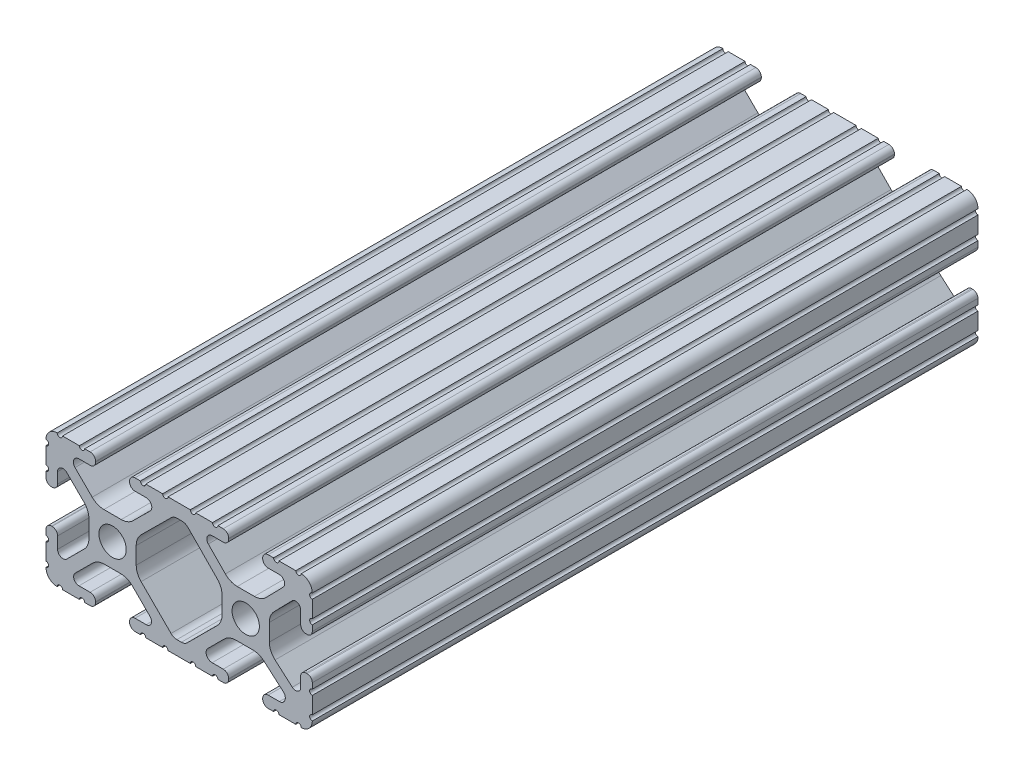
SolidWorks part; units mm, degrees
ref_plane "Front Plane" through (0, 0, 0) normal (0, 0, 1) x (1, 0, 0)
ref_plane "Top Plane" through (0, 0, 0) normal (0, 1, 0) x (1, 0, 0)
ref_plane "Right Plane" through (0, 0, 0) normal (1, 0, 0) x (0, 0, -1)
sketch "Sketch1" plane through (0, 0, 0) normal (0, 0, 1) x (1, 0, 0)
  line L0 (-7.2595, -3.8694) -> (-1.5457, -9.5728)
  line L1 (-8.1915, 1.6223) -> (-8.1915, -1.6223)
  line L2 (-1.504, 9.5765) -> (-7.252, 3.8768)
  line L3 (0.5515, 10.033) -> (-0.3952, 10.033)
  line L4 (7.2829, 3.8459) -> (1.6756, 9.5611)
  line L5 (8.1915, -1.6223) -> (8.1915, 1.6223)
  line L6 (1.5457, -9.5728) -> (7.2595, -3.8694)
  line L7 (-0.4332, -10.033) -> (0.4332, -10.033)
  line L8 (18.0171, 12.7) -> (16.9875, 12.7)
  line L9 (15.9385, 11.651) -> (15.9385, 11.5392)
  line L10 (16.9875, 10.4902) -> (19.1164, 10.4902)
  line L11 (19.8441, 8.7652) -> (16.619, 5.4551)
  line L12 (14.3449, 4.4958) -> (11.0833, 4.4958)
  line L13 (8.817, 5.4472) -> (5.5642, 8.7627)
  line L14 (6.2894, 10.4902) -> (8.4125, 10.4902)
  line L15 (9.4615, 11.5392) -> (9.4615, 11.651)
  line L16 (8.4125, 12.7) -> (7.3829, 12.7)
  line L17 (6.3669, 12.7) -> (3.1496, 12.7)
  line L18 (2.1336, 12.7) -> (-2.1336, 12.7)
  line L19 (-3.1496, 12.7) -> (-6.3669, 12.7)
  line L20 (-7.3829, 12.7) -> (-8.4125, 12.7)
  line L21 (-9.4615, 11.651) -> (-9.4615, 11.5392)
  line L22 (-8.4125, 10.4902) -> (-6.2836, 10.4902)
  line L23 (-5.5326, 8.6661) -> (-8.81, 5.4163)
  line L24 (-11.0455, 4.4958) -> (-14.3545, 4.4958)
  line L25 (-16.59, 5.4163) -> (-19.8674, 8.6661)
  line L26 (-19.1164, 10.4902) -> (-16.9875, 10.4902)
  line L27 (-15.9385, 11.5392) -> (-15.9385, 11.651)
  line L28 (-16.9875, 12.7) -> (-18.0171, 12.7)
  line L29 (-19.0331, 12.7) -> (-22.2504, 12.7)
  line L30 (-25.4, 9.5504) -> (-25.4, 6.3331)
  line L31 (-25.4, 5.3171) -> (-25.4, 4.2375)
  line L32 (-24.401, 3.2385) -> (-24.2392, 3.2385)
  line L33 (-23.1902, 4.2875) -> (-23.1902, 6.3347)
  line L34 (-21.434, 7.0665) -> (-18.148, 3.8082)
  line L35 (-17.2085, 1.5536) -> (-17.2085, -1.6952)
  line L36 (-18.1405, -3.9423) -> (-21.4316, -7.2274)
  line L37 (-23.1902, -6.498) -> (-23.1902, -4.2875)
  line L38 (-24.2392, -3.2385) -> (-24.351, -3.2385)
  line L39 (-25.4, -4.2875) -> (-25.4, -5.3171)
  line L40 (-25.4, -6.3331) -> (-25.4, -9.5504)
  line L41 (-22.2504, -12.7) -> (-19.0331, -12.7)
  line L42 (-18.0171, -12.7) -> (-16.9875, -12.7)
  line L43 (-15.9384, -11.651) -> (-15.9384, -11.5392)
  line L44 (-16.9875, -10.4902) -> (-19.1164, -10.4902)
  line L45 (-19.8341, -8.7551) -> (-16.4966, -5.4237)
  line L46 (-14.2536, -4.4958) -> (-11.1464, -4.4958)
  line L47 (-8.9034, -5.4237) -> (-5.5659, -8.7551)
  line L48 (-6.2836, -10.4902) -> (-8.4125, -10.4902)
  line L49 (-9.4616, -11.5392) -> (-9.4616, -11.651)
  line L50 (-8.4125, -12.7) -> (-7.3829, -12.7)
  line L51 (-6.3669, -12.7) -> (-3.1496, -12.7)
  line L52 (-2.1336, -12.7) -> (2.1336, -12.7)
  line L53 (3.1496, -12.7) -> (6.3669, -12.7)
  line L54 (7.3829, -12.7) -> (8.4125, -12.7)
  line L55 (9.4616, -11.651) -> (9.4616, -11.5392)
  line L56 (8.4125, -10.4902) -> (6.2894, -10.4902)
  line L57 (5.4807, -8.5353) -> (8.5979, -5.4237)
  line L58 (10.8409, -4.4958) -> (14.1026, -4.4958)
  line L59 (16.1879, -5.2766) -> (19.8682, -8.4822)
  line L60 (19.1164, -10.4902) -> (16.9875, -10.4902)
  line L61 (15.9384, -11.5392) -> (15.9384, -11.651)
  line L62 (16.9875, -12.7) -> (18.0171, -12.7)
  line L63 (19.0331, -12.7) -> (22.2504, -12.7)
  line L64 (25.4, -9.5504) -> (25.4, -6.3331)
  line L65 (25.4, -5.3171) -> (25.4, -4.2375)
  line L66 (24.401, -3.2385) -> (24.1892, -3.2385)
  line L67 (23.1902, -4.2375) -> (23.1902, -6.1559)
  line L68 (21.584, -6.8869) -> (18.2982, -4.025)
  line L69 (17.2085, -1.6308) -> (17.2085, 1.6308)
  line L70 (18.1094, 3.8465) -> (21.5263, 7.3534)
  line L71 (23.1902, 6.6769) -> (23.1902, 4.2375)
  line L72 (24.1892, 3.2385) -> (24.401, 3.2385)
  line L73 (25.4, 4.2375) -> (25.4, 5.3171)
  line L74 (25.4, 6.3332) -> (25.4, 9.5504)
  line L75 (22.2504, 12.7) -> (19.0331, 12.7)
  circle A0 centre (-12.7, 0) radius 2.6035
  circle A1 centre (12.7, 0) radius 2.6035
  arc A2 (-1.5457, -9.5728) -> (-0.4332, -10.033) centre (-0.4332, -8.4582) ccw
  arc A3 (-8.1915, -1.6223) -> (-7.2595, -3.8694) centre (-5.0165, -1.6223) ccw
  arc A4 (-7.252, 3.8768) -> (-8.1915, 1.6223) centre (-5.0165, 1.6223) ccw
  arc A5 (-0.3952, 10.033) -> (-1.504, 9.5765) centre (-0.3952, 8.4582) ccw
  arc A6 (1.6756, 9.5611) -> (0.5515, 10.033) centre (0.5515, 8.4582) ccw
  arc A7 (8.1915, 1.6223) -> (7.2829, 3.8459) centre (5.0165, 1.6223) ccw
  arc A8 (7.2595, -3.8694) -> (8.1915, -1.6223) centre (5.0165, -1.6223) ccw
  arc A9 (0.4332, -10.033) -> (1.5457, -9.5728) centre (0.4332, -8.4582) ccw
  arc A10 (18.0171, 12.7) -> (19.0331, 12.7) centre (18.5251, 12.7) ccw
  arc A11 (16.9875, 12.7) -> (15.9385, 11.651) centre (16.9875, 11.651) ccw
  arc A12 (15.9385, 11.5392) -> (16.9875, 10.4902) centre (16.9875, 11.5392) ccw
  arc A13 (19.8441, 8.7652) -> (19.1164, 10.4902) centre (19.1164, 9.4742) ccw
  arc A14 (14.3449, 4.4958) -> (16.619, 5.4551) centre (14.3449, 7.6708) ccw
  arc A15 (8.817, 5.4472) -> (11.0833, 4.4958) centre (11.0833, 7.6708) ccw
  arc A16 (6.2894, 10.4902) -> (5.5642, 8.7627) centre (6.2894, 9.4742) ccw
  arc A17 (8.4125, 10.4902) -> (9.4615, 11.5392) centre (8.4125, 11.5392) ccw
  arc A18 (9.4615, 11.651) -> (8.4125, 12.7) centre (8.4125, 11.651) ccw
  arc A19 (6.3669, 12.7) -> (7.3829, 12.7) centre (6.8749, 12.7) ccw
  arc A20 (2.1336, 12.7) -> (3.1496, 12.7) centre (2.6416, 12.7) ccw
  arc A21 (-3.1496, 12.7) -> (-2.1336, 12.7) centre (-2.6416, 12.7) ccw
  arc A22 (-7.3829, 12.7) -> (-6.3669, 12.7) centre (-6.8749, 12.7) ccw
  arc A23 (-8.4125, 12.7) -> (-9.4615, 11.651) centre (-8.4125, 11.651) ccw
  arc A24 (-9.4615, 11.5392) -> (-8.4125, 10.4902) centre (-8.4125, 11.5392) ccw
  arc A25 (-5.5326, 8.6661) -> (-6.2836, 10.4902) centre (-6.2836, 9.4235) ccw
  arc A26 (-11.0455, 4.4958) -> (-8.81, 5.4163) centre (-11.0455, 7.6708) ccw
  arc A27 (-16.59, 5.4163) -> (-14.3545, 4.4958) centre (-14.3545, 7.6708) ccw
  arc A28 (-19.1164, 10.4902) -> (-19.8674, 8.6661) centre (-19.1164, 9.4235) ccw
  arc A29 (-16.9875, 10.4902) -> (-15.9385, 11.5392) centre (-16.9875, 11.5392) ccw
  arc A30 (-15.9385, 11.651) -> (-16.9875, 12.7) centre (-16.9875, 11.651) ccw
  arc A31 (-19.0331, 12.7) -> (-18.0171, 12.7) centre (-18.5251, 12.7) ccw
  arc A32 (-23.2664, 12.6998) -> (-22.2504, 12.7) centre (-22.7584, 12.7) ccw
  arc A33 (-23.2664, 12.6998) -> (-25.3998, 10.5664) centre (-23.2918, 10.5918) ccw
  arc A34 (-25.4, 9.5504) -> (-25.3998, 10.5664) centre (-25.4, 10.0584) ccw
  arc A35 (-25.4, 5.3171) -> (-25.4, 6.3331) centre (-25.4, 5.8251) ccw
  arc A36 (-25.4, 4.2375) -> (-24.401, 3.2385) centre (-24.401, 4.2375) ccw
  arc A37 (-24.2392, 3.2385) -> (-23.1902, 4.2875) centre (-24.2392, 4.2875) ccw
  arc A38 (-21.434, 7.0665) -> (-23.1902, 6.3347) centre (-22.1596, 6.3347) ccw
  arc A39 (-17.2085, 1.5536) -> (-18.148, 3.8082) centre (-20.3835, 1.5536) ccw
  arc A40 (-18.1405, -3.9423) -> (-17.2085, -1.6952) centre (-20.3835, -1.6952) ccw
  arc A41 (-23.1902, -6.498) -> (-21.4316, -7.2274) centre (-22.1596, -6.498) ccw
  arc A42 (-23.1902, -4.2875) -> (-24.2392, -3.2385) centre (-24.2392, -4.2875) ccw
  arc A43 (-24.351, -3.2385) -> (-25.4, -4.2875) centre (-24.351, -4.2875) ccw
  arc A44 (-25.4, -6.3331) -> (-25.4, -5.3171) centre (-25.4, -5.8251) ccw
  arc A45 (-25.3998, -10.5664) -> (-25.4, -9.5504) centre (-25.4, -10.0584) ccw
  arc A46 (-25.3998, -10.5664) -> (-23.2664, -12.6998) centre (-23.2918, -10.5918) ccw
  arc A47 (-22.2504, -12.7) -> (-23.2664, -12.6998) centre (-22.7584, -12.7) ccw
  arc A48 (-18.0171, -12.7) -> (-19.0331, -12.7) centre (-18.5251, -12.7) ccw
  arc A49 (-16.9875, -12.7) -> (-15.9384, -11.651) centre (-16.9875, -11.651) ccw
  arc A50 (-15.9384, -11.5392) -> (-16.9875, -10.4902) centre (-16.9875, -11.5392) ccw
  arc A51 (-19.8341, -8.7551) -> (-19.1164, -10.4902) centre (-19.1164, -9.4742) ccw
  arc A52 (-14.2536, -4.4958) -> (-16.4966, -5.4237) centre (-14.2536, -7.6708) ccw
  arc A53 (-8.9034, -5.4237) -> (-11.1464, -4.4958) centre (-11.1464, -7.6708) ccw
  arc A54 (-6.2836, -10.4902) -> (-5.5659, -8.7551) centre (-6.2836, -9.4742) ccw
  arc A55 (-8.4125, -10.4902) -> (-9.4616, -11.5392) centre (-8.4125, -11.5392) ccw
  arc A56 (-9.4616, -11.651) -> (-8.4125, -12.7) centre (-8.4125, -11.651) ccw
  arc A57 (-6.3669, -12.7) -> (-7.3829, -12.7) centre (-6.8749, -12.7) ccw
  arc A58 (-2.1336, -12.7) -> (-3.1496, -12.7) centre (-2.6416, -12.7) ccw
  arc A59 (3.1496, -12.7) -> (2.1336, -12.7) centre (2.6416, -12.7) ccw
  arc A60 (7.3829, -12.7) -> (6.3669, -12.7) centre (6.8749, -12.7) ccw
  arc A61 (8.4125, -12.7) -> (9.4616, -11.651) centre (8.4125, -11.651) ccw
  arc A62 (9.4616, -11.5392) -> (8.4125, -10.4902) centre (8.4125, -11.5392) ccw
  arc A63 (5.4807, -8.5353) -> (6.2894, -10.4902) centre (6.2894, -9.3455) ccw
  arc A64 (10.8409, -4.4958) -> (8.5979, -5.4237) centre (10.8409, -7.6708) ccw
  arc A65 (16.1879, -5.2766) -> (14.1026, -4.4958) centre (14.1026, -7.6708) ccw
  arc A66 (19.1164, -10.4902) -> (19.8682, -8.4822) centre (19.1164, -9.3455) ccw
  arc A67 (16.9875, -10.4902) -> (15.9384, -11.5392) centre (16.9875, -11.5392) ccw
  arc A68 (15.9384, -11.651) -> (16.9875, -12.7) centre (16.9875, -11.651) ccw
  arc A69 (19.0331, -12.7) -> (18.0171, -12.7) centre (18.5251, -12.7) ccw
  arc A70 (23.2664, -12.6998) -> (22.2504, -12.7) centre (22.7584, -12.7) ccw
  arc A71 (23.2664, -12.6998) -> (25.3998, -10.5664) centre (23.2918, -10.5918) ccw
  arc A72 (25.4, -9.5504) -> (25.3998, -10.5664) centre (25.4, -10.0584) ccw
  arc A73 (25.4, -5.3171) -> (25.4, -6.3331) centre (25.4, -5.8251) ccw
  arc A74 (25.4, -4.2375) -> (24.401, -3.2385) centre (24.401, -4.2375) ccw
  arc A75 (24.1892, -3.2385) -> (23.1902, -4.2375) centre (24.1892, -4.2375) ccw
  arc A76 (21.584, -6.8869) -> (23.1902, -6.1559) centre (22.2207, -6.1559) ccw
  arc A77 (17.2085, -1.6308) -> (18.2982, -4.025) centre (20.3835, -1.6308) ccw
  arc A78 (18.1094, 3.8465) -> (17.2085, 1.6308) centre (20.3835, 1.6308) ccw
  arc A79 (23.1902, 6.6769) -> (21.5263, 7.3534) centre (22.2207, 6.6769) ccw
  arc A80 (23.1902, 4.2375) -> (24.1892, 3.2385) centre (24.1892, 4.2375) ccw
  arc A81 (24.401, 3.2385) -> (25.4, 4.2375) centre (24.401, 4.2375) ccw
  arc A82 (25.4, 6.3332) -> (25.4, 5.3171) centre (25.4, 5.8251) ccw
  arc A83 (25.3998, 10.5664) -> (25.4, 9.5504) centre (25.4, 10.0584) ccw
  arc A84 (25.3998, 10.5664) -> (23.2664, 12.6998) centre (23.2918, 10.5918) ccw
  arc A85 (22.2504, 12.7) -> (23.2664, 12.6998) centre (22.7584, 12.7) ccw
  point P248 (0, 10.033)
extrude "Boss-Extrude1" add sketch "Sketch1" along normal mid plane 127
